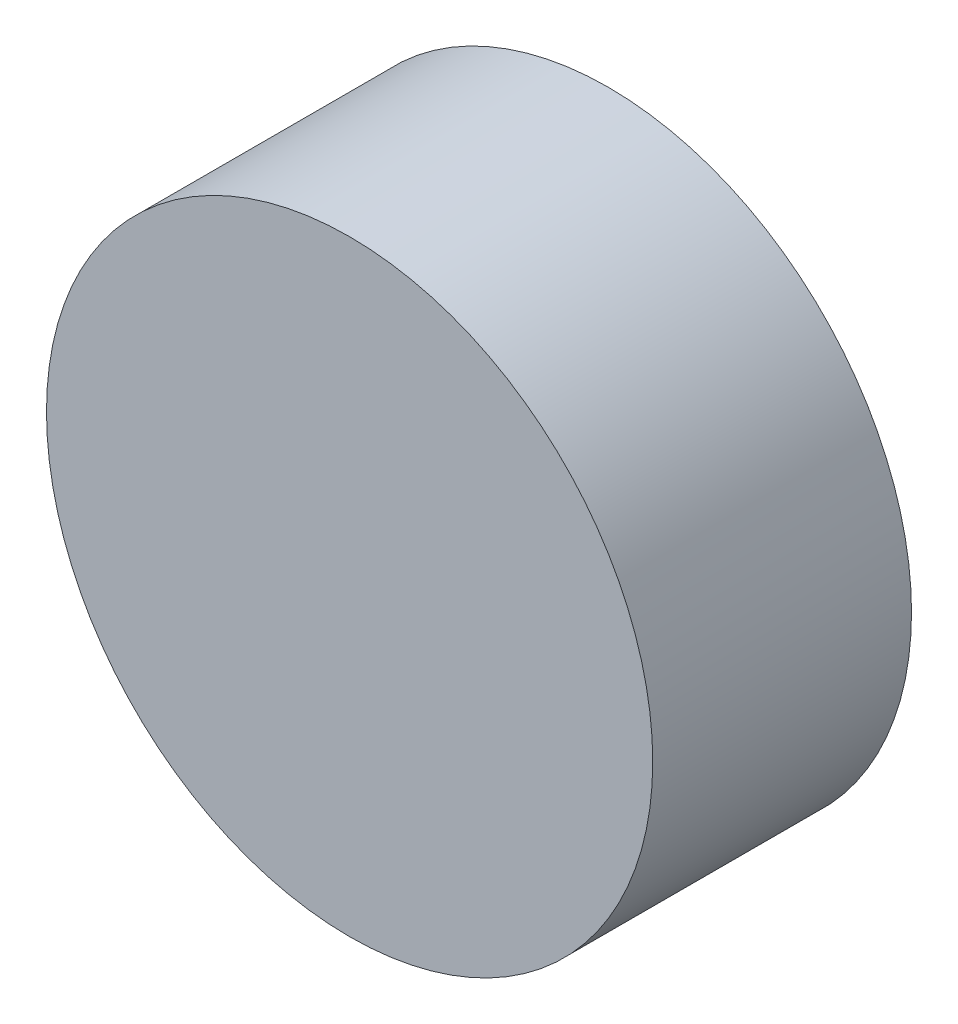
SolidWorks part; units mm, degrees
ref_plane "Front Plane" through (0, 0, 0) normal (0, 0, 1) x (1, 0, 0)
ref_plane "Top Plane" through (0, 0, 0) normal (0, 1, 0) x (1, 0, 0)
ref_plane "Right Plane" through (0, 0, 0) normal (1, 0, 0) x (0, 0, -1)
sketch "Sketch1" plane through (0, 0, 0) normal (0, 0, 1) x (1, 0, 0)
  circle A0 centre (0, 0) radius 32.8
  dimension "D1" = 65.6
extrude "Boss-Extrude1" add sketch "Sketch1" along normal blind 28
